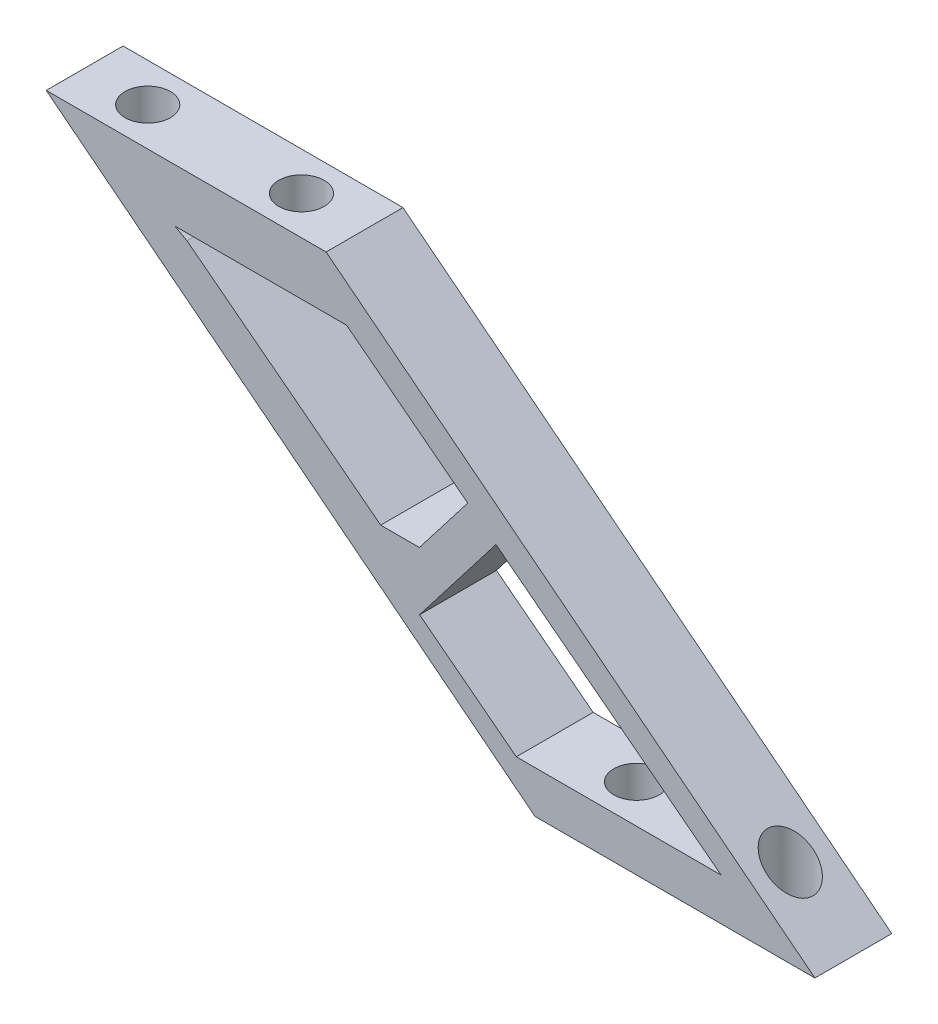
SolidWorks part; units mm, degrees
ref_plane "Front Plane" through (0, 0, 0) normal (0, 0, 1) x (1, 0, 0)
ref_plane "Top Plane" through (0, 0, 0) normal (0, 1, 0) x (1, 0, 0)
ref_plane "Right Plane" through (0, 0, 0) normal (1, 0, 0) x (0, 0, -1)
sketch "Sketch1" plane through (0, 0, 0) normal (0, 0, 1) x (1, 0, 0)
  line L0 (-22.6564, 16.4613) -> (-4.1596, 16.4613)
  line L1 (-4.1596, 16.4613) -> (28.1436, -8.9387)
  line L2 (28.1436, -8.9387) -> (9.6467, -8.9387)
  line L3 (9.6467, -8.9387) -> (-22.6564, 16.4613)
  line L4 (-13.3567, 12.5087) -> (-0.5532, 2.6317)
  line L5 (-0.5532, 2.6317) -> (2.0075, 2.6317)
  line L6 (2.0075, 2.6317) -> (5.201, 6.7715)
  line L7 (5.201, 6.7715) -> (-2.806, 12.9484)
  line L8 (-2.806, 12.9484) -> (-14.1615, 12.9484)
  line L9 (-14.1615, 12.9484) -> (-13.3567, 12.5087)
  line L10 (2.0175, -1.2139) -> (8.4094, -6.1448)
  line L11 (8.4094, -6.1448) -> (21.9444, -6.1448)
  line L12 (21.9444, -6.1448) -> (7.0672, 5.3319)
  line L13 (7.0672, 5.3319) -> (2.0175, -1.2139)
  point P12 (0, 0)
  dimension "D1" = 25.4
  dimension "D2" = 50.8
extrude "Boss-Extrude1" add sketch "Sketch1" along normal blind 5.08
sketch "Sketch2" plane through (0, 16.4613, 0) normal (0, 1, 0) x (1, 0, 0)
  line L0 (-22.6564, -2.54) -> (-4.1596, -2.54) construction
  line L1 (-22.6564, -5.08) -> (-22.6564, 0) construction
  line L2 (-4.1596, -5.08) -> (-4.1596, 0) construction
  circle A0 centre (-18.488, -2.54) radius 1.5
  circle A1 centre (-8.328, -2.54) radius 1.5
  point P8 (-13.408, -2.54)
  dimension "D1" = 3
  dimension "D3" = 3
  dimension "D2" = 5.08
  dimension "D4" = 5.08
extrude "Cut-Extrude1" cut sketch "Sketch2" against normal blind 5.08
sketch "Sketch3" plane through (0, -8.9387, 0) normal (0, -1, 0) x (-1, 0, 0)
  line L0 (-28.1436, -2.54) -> (-9.6467, -2.54) construction
  line L1 (-28.1436, -5.08) -> (-28.1436, 0) construction
  line L2 (-9.6467, -5.08) -> (-9.6467, 0) construction
  circle A0 centre (-23.9751, -2.54) radius 1.5
  circle A1 centre (-13.8151, -2.54) radius 1.5
  point P10 (-18.8951, -2.54)
  dimension "D1" = 3
  dimension "D2" = 3
  dimension "D3" = 5.08
  dimension "D4" = 5.08
extrude "Cut-Extrude2" cut sketch "Sketch3" against normal blind 6.604
